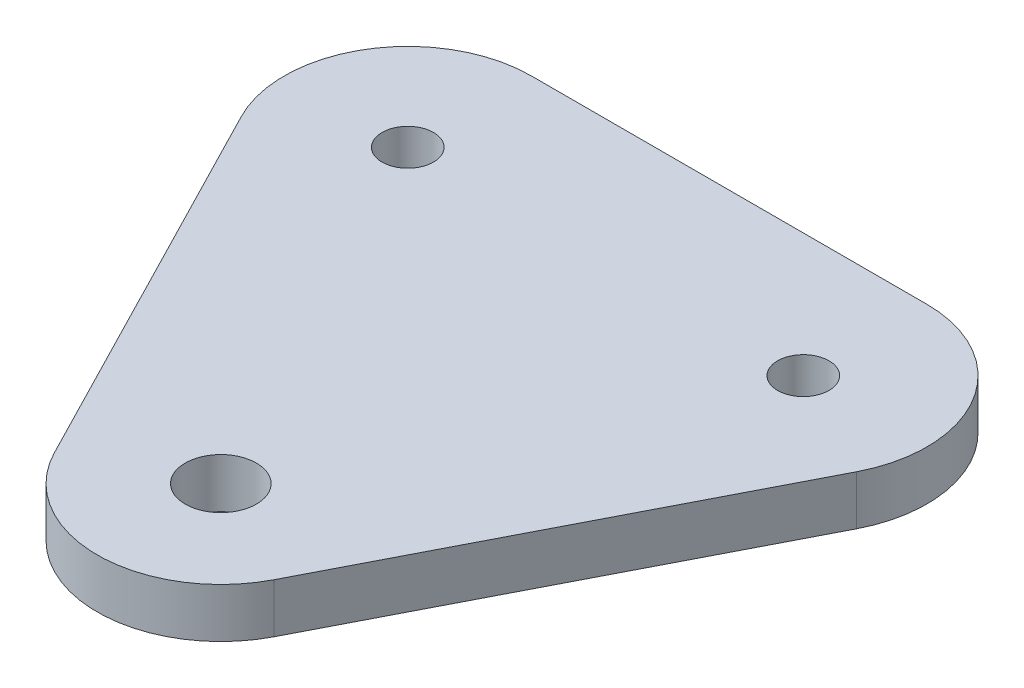
SolidWorks part; units mm, degrees
ref_plane "Front Plane" through (0, 0, 0) normal (0, 0, 1) x (1, 0, 0)
ref_plane "Top Plane" through (0, 0, 0) normal (0, 1, 0) x (1, 0, 0)
ref_plane "Right Plane" through (0, 0, 0) normal (1, 0, 0) x (0, 0, -1)
sketch "Sketch1" plane through (0, 0, 0) normal (0, 1, 0) x (1, 0, 0)
  line L0 (-31.1171, 8.6001) -> (-11.1151, -30.3099)
  line L1 (11.1196, -30.309) -> (31.1176, 8.601)
  line L2 (20, 26.8149) -> (-20, 26.8149)
  line L3 (-20, 14.3149) -> (0, 0) construction
  line L4 (0, 0) -> (20, 14.3149) construction
  line L5 (0.002, -24.5951) -> (0, 0) construction
  circle A0 centre (-20, 14.3149) radius 2.6
  circle A1 centre (20, 14.3149) radius 2.6
  circle A2 centre (0.002, -24.5951) radius 3.6
  arc A3 (-20, 26.8149) -> (-31.1171, 8.6001) centre (-20, 14.3149) ccw
  arc A4 (31.1176, 8.601) -> (20, 26.8149) centre (20, 14.3149) ccw
  arc A5 (-11.1151, -30.3099) -> (11.1196, -30.309) centre (0.002, -24.5951) ccw
  dimension "D4" = 5.2
  dimension "D5" = 25
  dimension "D6" = 7.2
  dimension "D1" = 40
  dimension "D2" = 43.7482
  dimension "D3" = 43.7501
extrude "Boss-Extrude1" add sketch "Sketch1" along normal blind 5
